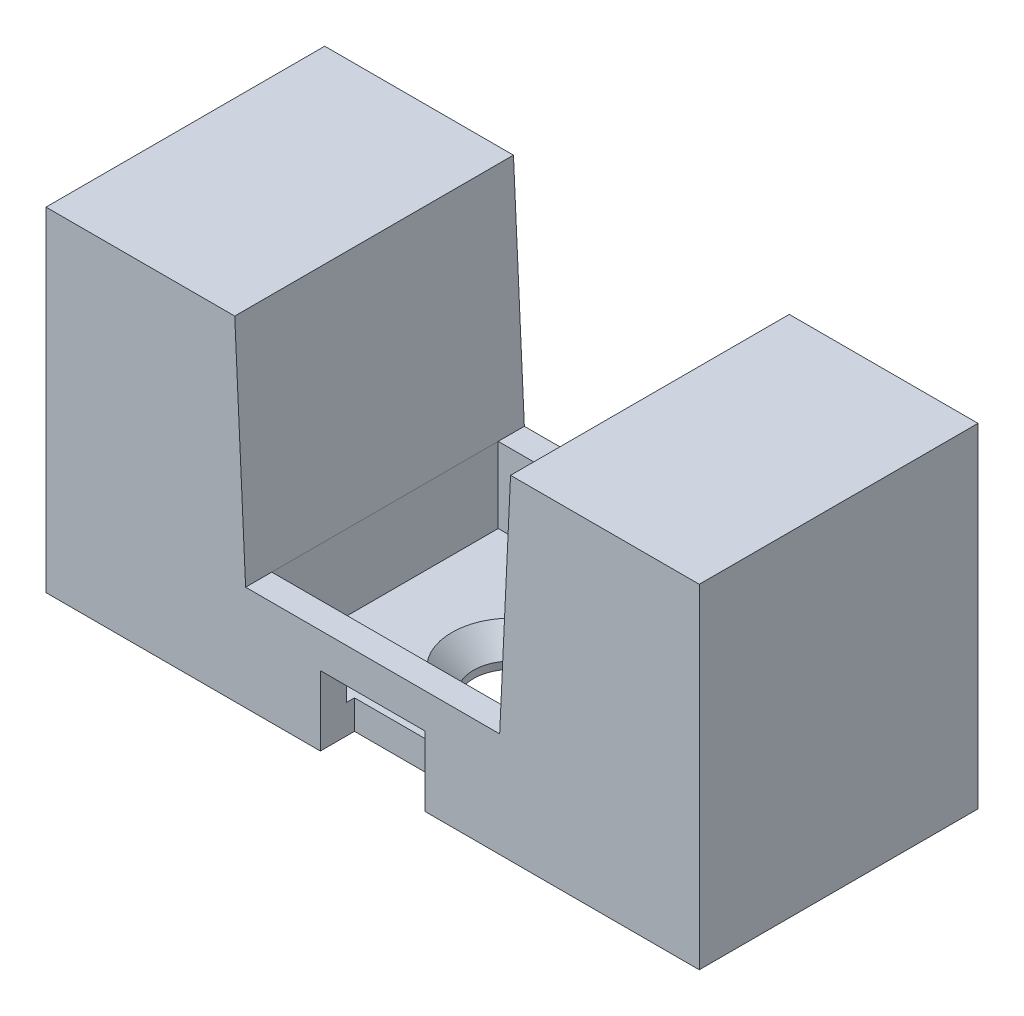
SolidWorks part; units mm, degrees
ref_plane "Front Plane" through (0, 0, 0) normal (0, 0, 1) x (1, 0, 0)
ref_plane "Top Plane" through (0, 0, 0) normal (0, 1, 0) x (1, 0, 0)
ref_plane "Right Plane" through (0, 0, 0) normal (1, 0, 0) x (0, 0, -1)
sketch "Sketch1" plane through (0, 0, 0) normal (0, 1, 0) x (1, 0, 0)
  line L1 (-11.25, 4.8) -> (11.25, 4.8)
  line L2 (-11.25, 4.8) -> (-11.25, -4.8)
  line L3 (-11.25, -4.8) -> (11.25, -4.8)
  line L4 (11.25, 4.8) -> (11.25, -4.8)
  line L5 (-11.25, 4.8) -> (11.25, -4.8) construction
  line L6 (-11.25, -4.8) -> (11.25, 4.8) construction
  point P0 (0, 0)
  dimension "D1" = 9.6
  dimension "D2" = 22.5
extrude "Boss-Extrude1" add sketch "Sketch1" along normal blind 11.5
sketch "Sketch3" plane through (0, 0, 4.8) normal (0, 0, 1) x (1, 0, 0)
  line L0 (4.75, 11.5) -> (4.375, 3.6)
  line L1 (-11.25, 11.5) -> (11.25, 11.5) construction
  line L2 (4.375, 3.6) -> (-4.375, 3.6)
  line L3 (-4.375, 3.6) -> (-4.75, 11.5)
  line L4 (-4.75, 11.5) -> (4.75, 11.5)
  line L5 (0, 3.6) -> (0, 11.5) construction
  line L7 (-11.25, 0) -> (11.25, 0) construction
  point P6 (0, 11.5)
  point P7 (0, 11.5)
  dimension "D1" = 9.5
  dimension "D2" = 8.75
  dimension "D3" = 3.6
extrude "Cut-Extrude1" cut sketch "Sketch3" against normal through all
sketch "Sketch4" plane through (0, 3.6, 0) normal (0, 1, 0) x (1, 0, 0)
  line L0 (-4.375, 4.8) -> (-4.375, -4.8) construction
  line L1 (-4.375, -3.9) -> (4.375, -3.9)
  line L2 (-4.375, -3.9) -> (-4.375, 3.9)
  line L3 (-4.375, 3.9) -> (4.375, 3.9)
  line L4 (4.375, -3.9) -> (4.375, 3.9)
  line L5 (-4.375, -3.9) -> (4.375, 3.9) construction
  line L6 (-4.375, 3.9) -> (4.375, -3.9) construction
  point P0 (0, 0)
  dimension "D1" = 7.8
extrude "Cut-Extrude2" cut sketch "Sketch4" against normal offset from surface (2.6 mm away) 1 up to face at (0, 0, 0)
sketch "Sketch5" plane through (0, 1, 0) normal (0, 1, 0) x (1, 0, 0)
  circle A0 centre (0, 0) radius 1.325
  dimension "D1" = 2.65
extrude "Cut-Extrude3" cut sketch "Sketch5" against normal through all
chamfer "Chamfer1" distance 0.75 angle 45 1 edges at (0, 1, 1.325)
sketch "Sketch6" plane through (0, 0, 0) normal (0, -1, 0) x (1, 0, 0)
  line L0 (-11.25, 4.8) -> (11.25, 4.8) construction
  line L1 (-1.8, 4.8) -> (1.8, 4.8)
  line L2 (-1.8, 4.8) -> (-1.8, 3.625)
  line L3 (-1.8, 3.625) -> (1.8, 3.625)
  line L4 (1.8, 4.8) -> (1.8, 3.625)
  point P6 (0, 4.8)
  point P8 (0, 4.8)
  dimension "D1" = 1.175
  dimension "D2" = 3.6
extrude "Cut-Extrude4" cut sketch "Sketch6" against normal blind 2.4
mirror "Mirror1" about plane through (0, 0, 0) normal (0, 0, 1) of "Cut-Extrude4"
